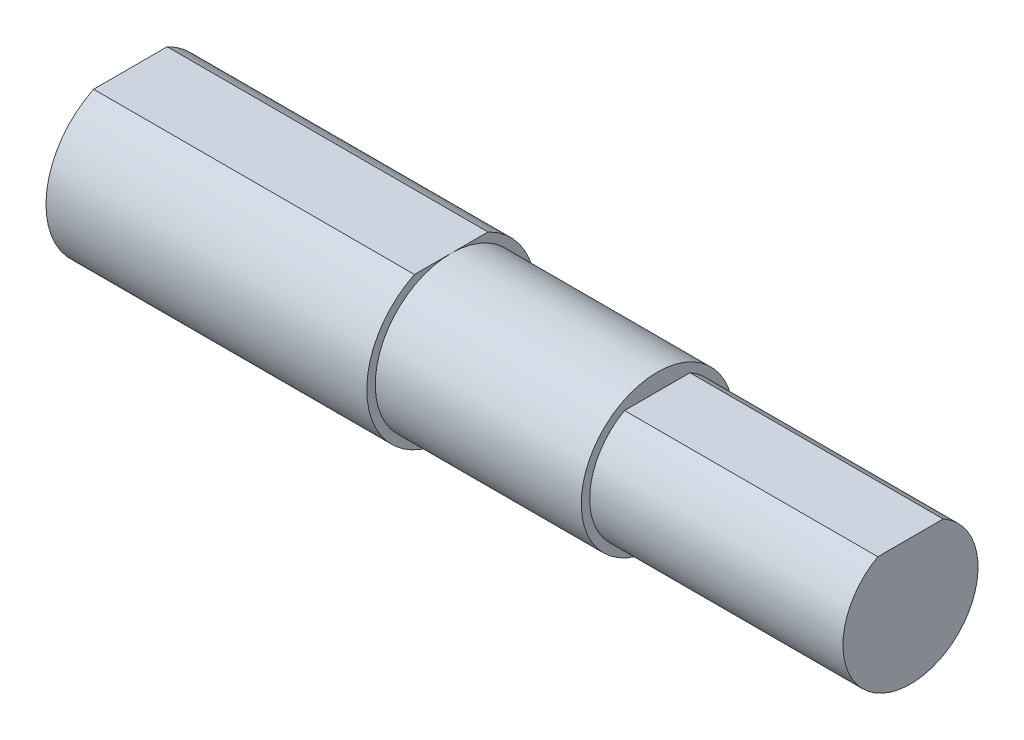
SolidWorks part; units mm, degrees
ref_plane "前视基准面" through (0, 0, 0) normal (0, 0, 1) x (1, 0, 0)
ref_plane "上视基准面" through (0, 0, 0) normal (0, 1, 0) x (1, 0, 0)
ref_plane "右视基准面" through (0, 0, 0) normal (1, 0, 0) x (0, 0, -1)
sketch "草图1" plane through (0, 0, 0) normal (1, 0, 0) x (0, 0, -1)
  line L0 (-2.1794, 4.5) -> (2.1794, 4.5)
  arc A0 (-2.1794, 4.5) -> (2.1794, 4.5) centre (0, 0) ccw
  dimension "D1" = 5
  dimension "D2" = 4.5
extrude "拉伸1" add sketch "草图1" along normal blind 19
sketch "草图2" plane through (19, 0, 0) normal (1, 0, 0) x (0, 0, -1)
  circle A0 centre (0, 0) radius 4.5
  dimension "D1" = 9
extrude "拉伸2" add sketch "草图2" along normal blind 12.2
sketch "草图3" plane through (31.2, 0, 0) normal (1, 0, 0) x (0, 0, -1)
  line L0 (-1.9365, 3.5) -> (1.9365, 3.5)
  arc A0 (-1.9365, 3.5) -> (1.9365, 3.5) centre (0, 0) ccw
  dimension "D1" = 8
  dimension "D2" = 3.5
extrude "拉伸3" add sketch "草图3" along normal blind 15
